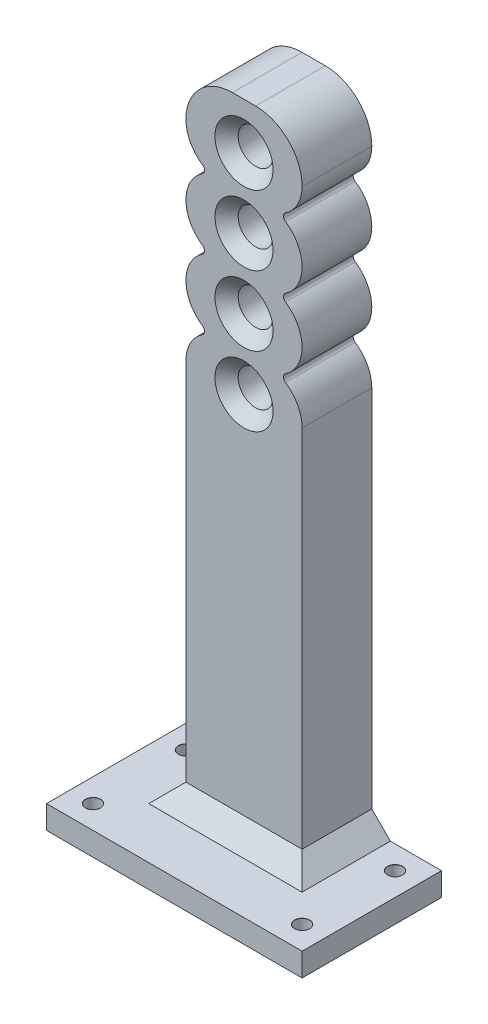
SolidWorks part; units mm, degrees
ref_plane "Front Plane" through (0, 0, 0) normal (0, 0, 1) x (1, 0, 0)
ref_plane "Top Plane" through (0, 0, 0) normal (0, 1, 0) x (1, 0, 0)
ref_plane "Right Plane" through (0, 0, 0) normal (1, 0, 0) x (0, 0, -1)
sketch "Sketch1" plane through (0, 0, 0) normal (0, 0, 1) x (1, 0, 0)
  line L0 (0, 0) -> (-12.5, 0)
  line L1 (-12.5, 0) -> (-12.5, 142.5)
  line L3 (12.5, 142.5) -> (12.5, 0)
  line L4 (12.5, 0) -> (0, 0)
  line L5 (0, 0) -> (0, 132.5) construction
  line L8 (-12.5, 142.5) -> (12.5, 142.5)
  circle A1 centre (0, 132.5) radius 3.75
  circle A2 centre (0, 117.5) radius 3.75
  circle A3 centre (0, 102.5) radius 3.75
  circle A4 centre (0, 87.5) radius 3.75
  point P3 (0, 106.4753)
  dimension "D5" = 7.5
  dimension "D1" = 25
  dimension "D2" = 132.5
  dimension "D3" = 10
  dimension "D4" = 4
  dimension "D6" = 15
extrude "Boss-Extrude1" add sketch "Sketch1" along normal blind 15
sketch "Sketch2" plane through (0, 0, 0) normal (0, 0, -1) x (-1, 0, 0)
  line L0 (-27.5, 5) -> (27.5, 5)
  line L4 (-27.5, 0) -> (-27.5, 5)
  line L8 (27.5, 0) -> (27.5, 5)
  line L9 (27.5, 0) -> (-27.5, 0)
  line L10 (12.5, 142.5) -> (12.5, 0) construction
  point P0 (0, 0)
  dimension "D1" = 15
  dimension "D2" = 5
extrude "Boss-Extrude2" add sketch "Sketch2" against normal blind 30
sketch "Sketch5" plane through (0, 5, 0) normal (0, 1, 0) x (1, 0, 0)
  line L0 (-27.5, 0) -> (-12.5, 0) construction
  line L1 (-27.5, -30) -> (27.5, -30) construction
  line L2 (-27.5, -30) -> (-27.5, 0) construction
  line L3 (27.5, -30) -> (27.5, 0) construction
  point P0 (-22.5, -5)
  point P2 (-22.5, -25)
  point P4 (22.5, -25)
  point P6 (22.5, -5)
  dimension "D1" = 5
  dimension "D2" = 5
  dimension "D3" = 5
  dimension "D4" = 5
hole_wizard "Ø3.2 (3.2) Diameter Hole1" positions "Sketch5" profile "Sketch4" hole size "Ø3.2" standard "ANSI Metric" end condition through all
sketch "Sketch4" plane through (-22.5, 5, 5) normal (1, 0, 0) x (0, 0, 1)
  line L0 (0, 0) -> (0, 5)
  line L1 (0, 5) -> (1.6, 5)
  line L2 (1.6, 5) -> (1.6, 0.025)
  line L3 (1.6, 0.025) -> (1.625, 0)
  line L5 (1.625, 0) -> (0, 0)
  line L6 (-1.6, 0.025) -> (-1.625, 0) construction
  line L11 (0, -6.35) -> (0, 107.95) construction
  dimension "Thru Hole Dia." = 3.2
  dimension "Thru Hole Depth" = 5
  dimension "Near C'Sink Dia." = 3.25
  dimension "Near C'Sink Angle" = 90
chamfer "Chamfer1" distance 4 angle 45 3 edges at (12.5, 5, 7.5) (-12.5, 5, 7.5) (0, 5, 15)
sketch "Sketch6" plane through (0, 0, 15) normal (0, 0, 1) x (1, 0, 0)
  line L0 (12.5, 142.5) -> (-12.5, 142.5) construction
  line L1 (-12.5, 142.5) -> (-12.5, 9) construction
  line L2 (0, 142.5) -> (0, 0) construction
  line L3 (12.5, 125) -> (-12.5, 125) construction
  line L4 (12.5, 132.5) -> (-12.5, 132.5) construction
  line L5 (-12.5, 132.5) -> (-12.5, 117.5)
  line L6 (-12.5, 117.5) -> (-12.5, 110.6941) construction
  line L7 (-2.5, 142.5) -> (-12.5, 142.5)
  line L8 (-12.5, 142.5) -> (-12.5, 132.5)
  line L9 (-2.5, 142.5) -> (2.5, 142.5) construction
  line L10 (-12.5, 117.5) -> (-12.5, 102.5)
  line L11 (-12.5, 102.5) -> (-12.5, 87.5)
  line L12 (12.5, 117.5) -> (12.5, 110.6941) construction
  line L13 (12.5, 102.5) -> (12.5, 87.5)
  line L14 (12.5, 117.5) -> (12.5, 102.5)
  line L15 (12.5, 142.5) -> (12.5, 132.5)
  line L16 (2.5, 142.5) -> (12.5, 142.5)
  line L17 (12.5, 132.5) -> (12.5, 117.5)
  arc A0 (-2.5, 142.5) -> (-12.5, 132.5) centre (-2.5, 132.5) ccw
  arc A1 (-12.5, 132.5) -> (-8.9429, 125.8304) centre (-4.4687, 132.5) ccw
  arc A2 (-8.9429, 125.8304) -> (-8.9429, 124.1696) centre (-9.5, 125) cw
  arc A3 (-8.9429, 124.1696) -> (-12.5, 117.5) centre (-4.4687, 117.5) ccw
  arc A4 (-12.5, 117.5) -> (-8.9429, 110.8304) centre (-4.4687, 117.5) ccw
  circle A5 centre (0, 132.5) radius 3.75 construction
  circle A6 centre (0, 117.5) radius 3.75 construction
  arc A7 (-8.9429, 109.1696) -> (-12.5, 102.5) centre (-4.4687, 102.5) ccw
  arc A8 (-8.9429, 110.8304) -> (-8.9429, 109.1696) centre (-9.5, 110) cw
  arc A9 (-12.5, 102.5) -> (-8.9429, 95.8304) centre (-4.4687, 102.5) ccw
  arc A10 (-8.9429, 94.1696) -> (-12.5, 87.5) centre (-4.4687, 87.5) ccw
  arc A11 (-8.9429, 95.8304) -> (-8.9429, 94.1696) centre (-9.5, 95) cw
  arc A12 (8.9429, 95.8304) -> (8.9429, 94.1696) centre (9.5, 95) ccw
  arc A13 (8.9429, 94.1696) -> (12.5, 87.5) centre (4.4687, 87.5) cw
  arc A14 (12.5, 102.5) -> (8.9429, 95.8304) centre (4.4687, 102.5) cw
  arc A15 (8.9429, 110.8304) -> (8.9429, 109.1696) centre (9.5, 110) ccw
  arc A16 (8.9429, 109.1696) -> (12.5, 102.5) centre (4.4687, 102.5) cw
  arc A17 (12.5, 117.5) -> (8.9429, 110.8304) centre (4.4687, 117.5) cw
  arc A18 (8.9429, 124.1696) -> (12.5, 117.5) centre (4.4687, 117.5) cw
  arc A19 (8.9429, 125.8304) -> (8.9429, 124.1696) centre (9.5, 125) ccw
  arc A20 (12.5, 132.5) -> (8.9429, 125.8304) centre (4.4687, 132.5) cw
  arc A21 (2.5, 142.5) -> (12.5, 132.5) centre (2.5, 132.5) cw
  point P20 (0, 0)
  point P44 (0, 132.5)
  point P45 (0, 125)
  point P62 (-2.5, 142.5)
  point P63 (-8.9429, 94.1696)
  point P64 (-12.5, 87.5)
  point P65 (-4.4687, 132.5)
  line M26 (-12.5, 142.5) -> (-12.5, 9)
  line M28 (12.5, 9) -> (12.5, 142.5)
  line M29 (12.5, 142.5) -> (-12.5, 142.5)
  dimension "D2" = 1
  dimension "D1" = 3
  dimension "D3" = 3
extrude "Cut-Extrude1" cut sketch "Sketch6" against normal through all both and the other way through all contours A8 A4 A7 M26 | A14 A12 A13 M28 | A17 A15 A16 M28 | A20 A19 A18 M28 | A21 M29 M28 | A0 M29 M26 | A3 A2 A1 M26 | L11 A10 A11 A9
chamfer "Chamfer2" distance 2.5 angle 45 4 edges at (3.75, 87.5, 15) (3.75, 102.5, 15) (3.75, 117.5, 15) (3.75, 132.5, 15)
